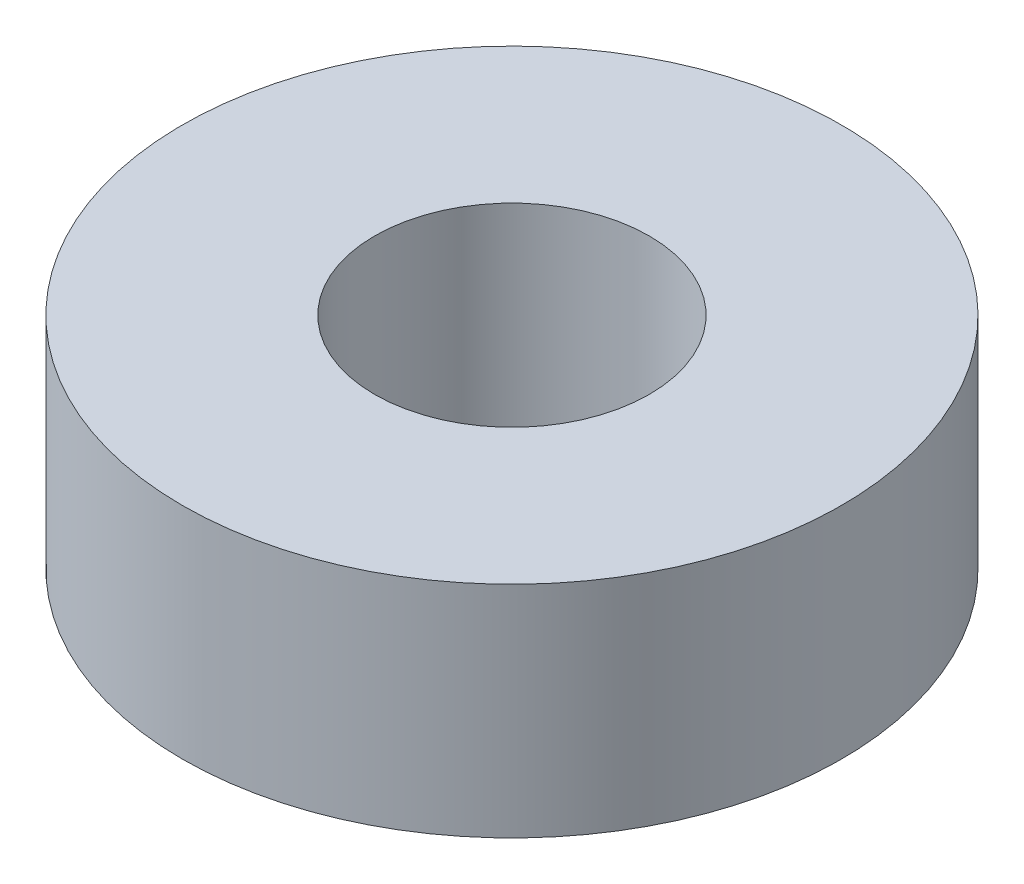
SolidWorks part; units mm, degrees
material "AISI 304"
ref_plane "前视基准面" through (0, 0, 0) normal (0, 0, 1) x (1, 0, 0)
ref_plane "上视基准面" through (0, 0, 0) normal (0, 1, 0) x (1, 0, 0)
ref_plane "右视基准面" through (0, 0, 0) normal (1, 0, 0) x (0, 0, -1)
other "Configuration Table"
sketch "草图1" plane through (0, 0, 0) normal (0, 1, 0) x (1, 0, 0)
  circle A0 centre (0, 0) radius 2.5
  circle A1 centre (0, 0) radius 6
  dimension "D1" = 5
  dimension "D2" = 12
extrude "凸台-拉伸1" add sketch "草图1" along normal blind 4
